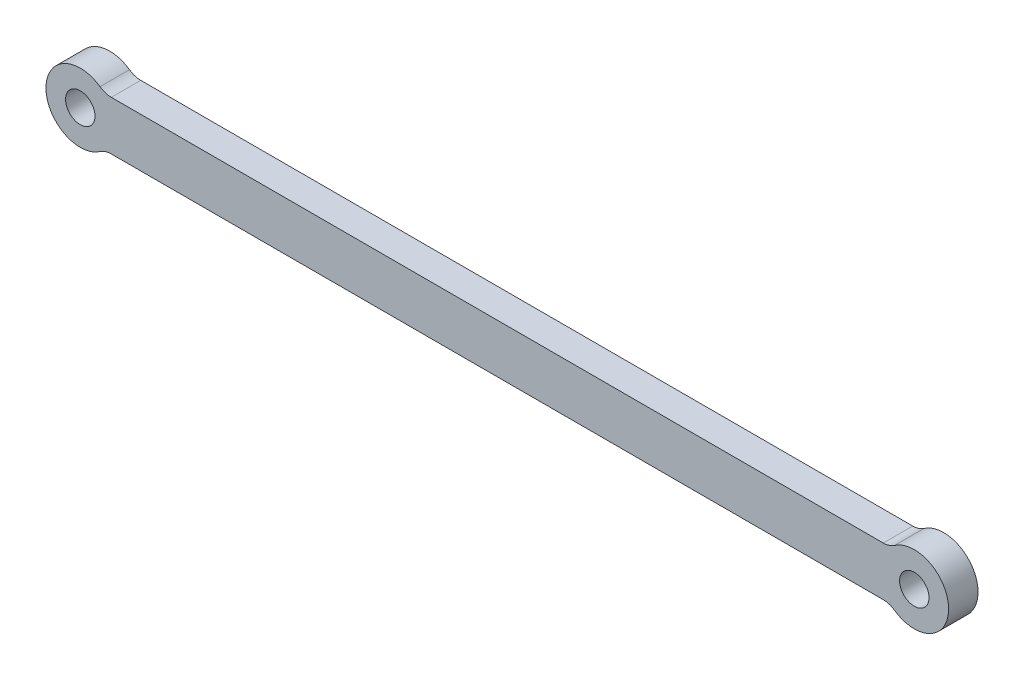
SolidWorks part; units mm, degrees
ref_plane "前视基准面" through (0, 0, 0) normal (0, 0, 1) x (1, 0, 0)
ref_plane "上视基准面" through (0, 0, 0) normal (0, 1, 0) x (1, 0, 0)
ref_plane "右视基准面" through (0, 0, 0) normal (1, 0, 0) x (0, 0, -1)
sketch "草图1" plane through (0, 0, 0) normal (0, 0, 1) x (1, 0, 0)
  line L0 (0, 0) -> (85, 0) construction
  line L1 (0, 3.5) -> (85, 3.5)
  line L2 (0, -3.5) -> (85, -3.5)
  arc A0 (0, 3.5) -> (0, -3.5) centre (0, 0) ccw
  arc A1 (85, -3.5) -> (85, 3.5) centre (85, 0) ccw
  circle A2 centre (0, 0) radius 1.5
  circle A3 centre (85, 0) radius 1.5
  point P3 (42.5, 0)
  dimension "D1" = 3
  dimension "D3" = 85
  dimension "D2" = 7
extrude "凸台-拉伸1" add sketch "草图1" along normal blind 3
sketch "草图2" plane through (0, 0, 3) normal (0, 0, 1) x (1, 0, 0)
  line L0 (42.5, 8.282) -> (42.5, -11.9927) construction
  line L1 (-6.0057, 0) -> (72.6728, 0) construction
  line L2 (3.1623, 2.5) -> (81.8377, 2.5)
  line L3 (3.1623, -2.5) -> (81.8377, -2.5)
  line L4 (0, 3.5) -> (85, 3.5)
  line L5 (0, -3.5) -> (85, -3.5)
  circle A0 centre (85, 0) radius 1.5 construction
  circle A1 centre (0, 0) radius 1.5 construction
  arc A2 (0, -3.5) -> (2.0124, -2.8636) centre (0, 0) ccw
  arc A3 (0, 3.5) -> (0, -3.5) centre (0, 0) ccw construction
  arc A4 (82.9876, 2.8636) -> (85, 3.5) centre (85, 0) cw
  arc A5 (2.0124, 2.8636) -> (0, 3.5) centre (0, 0) ccw
  arc A6 (85, -3.5) -> (82.9876, -2.8636) centre (85, 0) cw
  arc A7 (81.8377, -2.5) -> (82.9876, -2.8636) centre (81.8377, -4.5) cw
  arc A8 (81.8377, 2.5) -> (82.9876, 2.8636) centre (81.8377, 4.5) ccw
  arc A9 (3.1623, 2.5) -> (2.0124, 2.8636) centre (3.1623, 4.5) cw
  arc A10 (3.1623, -2.5) -> (2.0124, -2.8636) centre (3.1623, -4.5) ccw
  point P25 (82.5505, -2.5)
  point P28 (82.5505, 2.5)
  point P31 (2.4495, 2.5)
  point P34 (2.4495, -2.5)
  dimension "D1" = 5
  dimension "D2" = 2
extrude "切除-拉伸1" cut sketch "草图2" against normal through all
